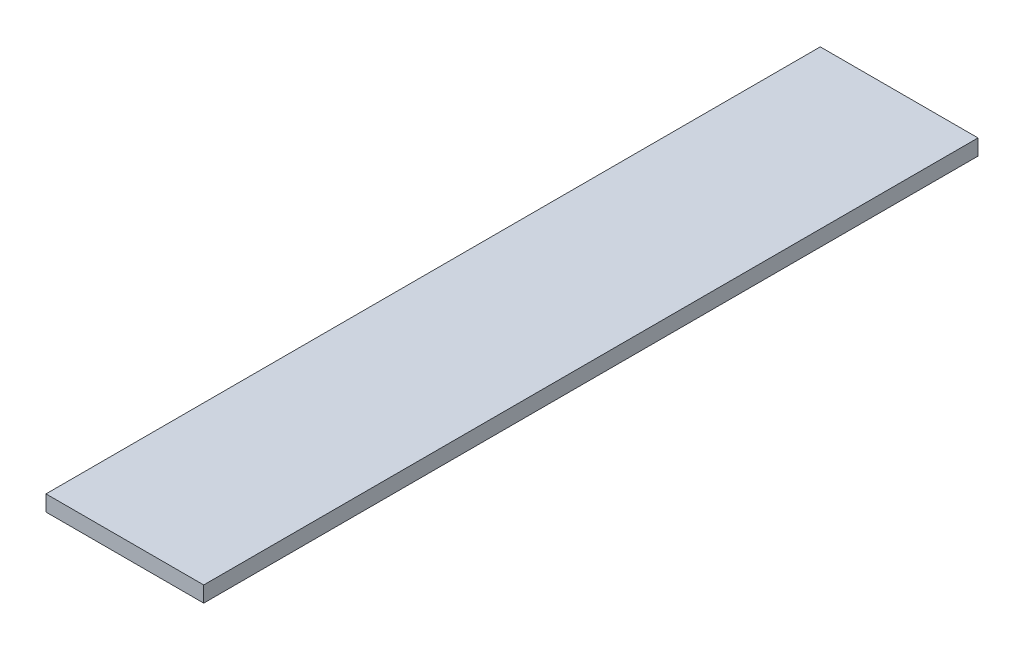
SolidWorks part; units mm, degrees
ref_plane "Płaszczyzna przednia" through (0, 0, 0) normal (0, 0, 1) x (1, 0, 0)
ref_plane "Płaszczyzna górna" through (0, 0, 0) normal (0, 1, 0) x (1, 0, 0)
ref_plane "Płaszczyzna prawa" through (0, 0, 0) normal (1, 0, 0) x (0, 0, -1)
sketch "Szkic1" plane through (0, 0, 0) normal (0, 0, 1) x (1, 0, 0)
  line L1 (0, 0) -> (50, 0)
  line L2 (0, 0) -> (0, 5)
  line L3 (0, 5) -> (50, 5)
  line L4 (50, 0) -> (50, 5)
  dimension "D1" = 50
  dimension "D2" = 5
extrude "Dodanie-wyciągnięcie1" add sketch "Szkic1" along normal blind 245.45
